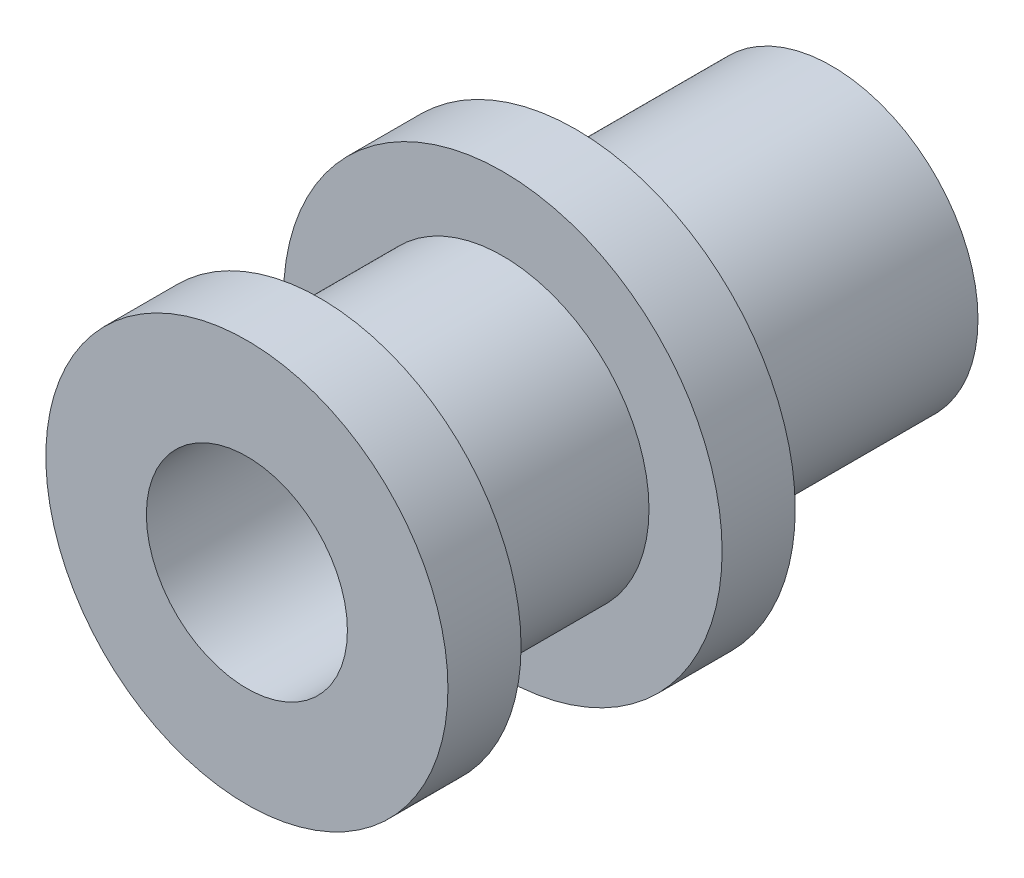
SolidWorks part; units mm, degrees
ref_plane "Front Plane" through (0, 0, 0) normal (0, 0, 1) x (1, 0, 0)
ref_plane "Top Plane" through (0, 0, 0) normal (0, 1, 0) x (1, 0, 0)
ref_plane "Right Plane" through (0, 0, 0) normal (1, 0, 0) x (0, 0, -1)
other "Configuration Table"
sketch "Sketch1" plane through (0, 0, 0) normal (0, 0, 1) x (1, 0, 0)
  circle A0 centre (0, 0) radius 5.5
  dimension "D1" = 11
extrude "Flange" add sketch "Sketch1" along normal blind 2
sketch "Sketch2" plane through (0, 0, 0) normal (0, 0, 1) x (1, 0, 0)
  circle A0 centre (0, 0) radius 4
  dimension "D1" = 8
extrude "Barrel" add sketch "Sketch2" along normal blind 14 from offset 14
sketch "Sketch3" plane through (0, 0, 0) normal (0, 0, 1) x (1, 0, 0)
  circle A0 centre (0, 0) radius 6
  dimension "D1" = 12
extrude "Nut" add sketch "Sketch3" along normal blind 2 from offset 7
sketch "Sketch4" plane through (0, 0, 0) normal (0, 0, 1) x (1, 0, 0)
  circle A0 centre (0, 0) radius 2.75
  dimension "D1" = 5.5
extrude "Socket" cut sketch "Sketch4" against normal blind 10 from offset 2
equation "\"Jar_OD\"= 90  'ASSUMED - Part G fallback - jar outer diameter"
equation "\"Jar_H\"= 120  'ASSUMED - Part G fallback - jar height"
equation "\"Pump_L\"= 45  'ASSUMED - Part G fallback"
equation "\"Pump_W\"= 24  'ASSUMED - Part G fallback"
equation "\"Pump_H\"= 33  'ASSUMED - Part G fallback"
equation "\"Pump_Outlet_OD\"= 7.5  'ASSUMED - Part G fallback"
equation "\"Tube_OD\"= 8  'ASSUMED - Part G fallback"
equation "\"Tube_ID\"= 6  'ASSUMED - Part G fallback"
equation "\"TDS_Body_Dia\"= 12  'ASSUMED - Part G fallback"
equation "\"TDS_Wet_Len\"= 45  'ASSUMED - Part G fallback - length in water"
equation "\"DS_Tube_Dia\"= 6  'ASSUMED - Part G fallback"
equation "\"DS_Tube_Len\"= 50  'ASSUMED - Part G fallback"
equation "\"ORP_Body_Dia\"= 12  'ASSUMED - Part G fallback"
equation "\"ORP_Body_Len\"= 150  'ASSUMED - Part G fallback"
equation "\"ORP_Cap_Dia\"= 16  'ASSUMED - Part G fallback"
equation "\"Turb_W\"= 33  'ASSUMED - Part G fallback - head width"
equation "\"Turb_D\"= 28  'ASSUMED - Part G fallback - head depth"
equation "\"Turb_H\"= 30  'ASSUMED - Part G fallback - head height"
equation "\"Turb_Slot_W\"= 10  'ASSUMED - Part G fallback - slot width"
equation "\"Flow_L\"= 62  'ASSUMED - Part G fallback YF-S201"
equation "\"Flow_W\"= 36  'ASSUMED - Part G fallback"
equation "\"Flow_H\"= 35  'ASSUMED - Part G fallback"
equation "\"Thread_G12_OD\"= 20.955  'ASSUMED - Part G fallback thread G1/2 (major diameter)"
equation "\"Valve_L\"= 75  'ASSUMED - Part G fallback"
equation "\"Valve_W\"= 45  'ASSUMED - Part G fallback"
equation "\"Valve_H\"= 60  'ASSUMED - Part G fallback"
equation "\"Tee_L\"= 40  'ASSUMED - Part G fallback - overall length"
equation "\"Tee_Branch_L\"= 25  'ASSUMED - Part G fallback"
equation "\"Tee_OD\"= 12  'ASSUMED - Part G fallback"
equation "\"LED_Board_L\"= 20  'ASSUMED - Part G fallback"
equation "\"LED_Board_W\"= 20  'ASSUMED - Part G fallback - LED at centre"
equation "\"GUVA_L\"= 20  'ASSUMED - Part G fallback"
equation "\"GUVA_W\"= 12  'ASSUMED - Part G fallback - sensor at centre"
equation "\"Reed_L\"= 27  'ASSUMED - Part G fallback MC-38 half"
equation "\"Reed_W\"= 14  'ASSUMED - Part G fallback"
equation "\"Reed_H\"= 8  'ASSUMED - Part G fallback"
equation "\"ESP_L\"= 51  'ASSUMED - Part G fallback"
equation "\"ESP_W\"= 28  'ASSUMED - Part G fallback"
equation "\"TFT_L\"= 58  'ASSUMED - Part G fallback - board"
equation "\"TFT_W\"= 35  'ASSUMED - Part G fallback - board"
equation "\"TFT_Win_L\"= 35  'ASSUMED - Part G fallback - visible window"
equation "\"TFT_Win_W\"= 28  'ASSUMED - Part G fallback - visible window"
equation "\"Relay_L\"= 50  'ASSUMED - Part G fallback"
equation "\"Relay_W\"= 26  'ASSUMED - Part G fallback"
equation "\"Relay_H\"= 19  'ASSUMED - Part G fallback"
equation "\"Mosfet_L\"= 34  'ASSUMED - Part G fallback"
equation "\"Mosfet_W\"= 17  'ASSUMED - Part G fallback"
equation "\"Mosfet_H\"= 12  'ASSUMED - Part G fallback"
equation "\"TDS_Board_L\"= 42  'ASSUMED - Part G fallback"
equation "\"TDS_Board_W\"= 32  'ASSUMED - Part G fallback"
equation "\"Turb_Board_L\"= 38  'ASSUMED - Part G fallback"
equation "\"Turb_Board_W\"= 28  'ASSUMED - Part G fallback"
equation "\"BNC_Thread_Dia\"= 9.5  'ASSUMED - Part G fallback"
equation "\"Plate_L\"= 420  'ASSUMED - Part G fallback"
equation "\"Plate_W\"= 297  'ASSUMED - Part G fallback"
equation "\"Plate_T\"= 6  'ASSUMED - Part G fallback"
equation "\"Booster_L\"= 150  'ASSUMED - Part G fallback - booster pump"
equation "\"Booster_W\"= 95  'ASSUMED - Part G fallback"
equation "\"Booster_H\"= 100  'ASSUMED - Part G fallback"
equation "\"PTube_OD\"= 6.35  'ASSUMED - Part G fallback - product tube 1/4 inch"
equation "\"Qz_Out\"= 12  'ASSUMED - Part G fallback - quartz channel outside square"
equation "\"Qz_Path\"= 10  'ASSUMED - Part G fallback - quartz channel inside light path"
equation "\"Qz_L\"= 40  'ASSUMED - Part G fallback - quartz channel length"
equation "\"LED860_Dia\"= 5  'ASSUMED - Part G fallback - 860 nm LED"
equation "\"BPW_L\"= 5.4  'ASSUMED - Part G fallback - BPW34"
equation "\"BPW_W\"= 4.3  'ASSUMED - Part G fallback - BPW34"
equation "\"Cart_Dia\"= 50  'ASSUMED - Part G fallback - sediment and pre-carbon cartridges"
equation "\"Cart_L\"= 255  'ASSUMED - Part G fallback"
equation "\"UF_Dia\"= 50  'ASSUMED - Part G fallback - UF cartridge"
equation "\"UF_L\"= 260  'ASSUMED - Part G fallback"
equation "\"RO_Dia\"= 62  'ASSUMED - Part G fallback - RO membrane housing"
equation "\"RO_L\"= 300  'ASSUMED - Part G fallback"
equation "\"UVC_Dia\"= 40  'ASSUMED - Part G fallback - UV-C chamber"
equation "\"UVC_L\"= 300  'ASSUMED - Part G fallback"
equation "\"Tank_W\"= 260  'ASSUMED - Part G fallback - storage tank"
equation "\"Tank_D\"= 160  'ASSUMED - Part G fallback"
equation "\"Tank_H\"= 300  'ASSUMED - Part G fallback"
equation "\"Cab_W\"= 400  'ASSUMED - Part G fallback - purifier cabinet"
equation "\"Cab_D\"= 270  'ASSUMED - Part G fallback"
equation "\"Cab_H\"= 560  'ASSUMED - Part G fallback"
equation "\"ORP_Board_L\"= 40  'ASSUMED - Part G fallback - ORP buffer board"
equation "\"ORP_Board_W\"= 30  'ASSUMED - Part G fallback"
equation "\"Opt_Board_L\"= 50  'ASSUMED - Part G fallback - optical front-end board"
equation "\"Opt_Board_W\"= 40  'ASSUMED - Part G fallback"
equation "\"Buck_L\"= 43  'ASSUMED - Part G fallback - 12 V to 5 V buck module"
equation "\"Buck_W\"= 21  'ASSUMED - Part G fallback"
equation "\"Buck_H\"= 14  'ASSUMED - Part G fallback"
equation "\"BB_L\"= 165  'ASSUMED - Part G fallback - breadboard (As_Built_R3 only)"
equation "\"BB_W\"= 55  'ASSUMED - Part G fallback"
equation "\"BB_H\"= 10  'ASSUMED - Part G fallback"
equation "\"Cuv_W\"= 12.5  'ASSUMED - old R3 cuvette (station suppressed in SS4)"
equation "\"Cuv_D\"= 12.5  'ASSUMED - old R3 cuvette (station suppressed in SS4)"
equation "\"Cuv_H\"= 45  'ASSUMED - old R3 cuvette (station suppressed in SS4)"
equation "\"Probe_Clr\"= 0.3  'DESIGN VALUE - Part C rule 3 - printed probe hole = diameter + 0.3"
equation "\"Label_H\"= 0.6  'DESIGN VALUE - Part D - raised label height"
